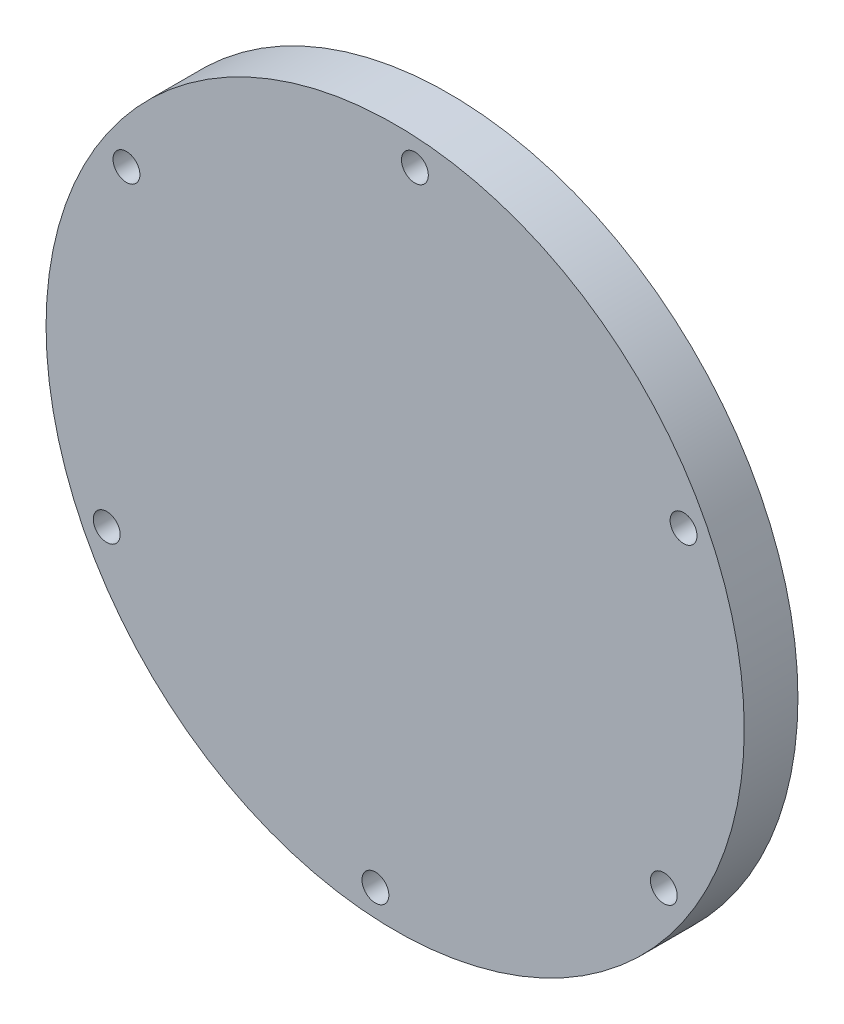
SolidWorks part; units mm, degrees
ref_plane "前视基准面" through (0, 0, 0) normal (0, 0, 1) x (1, 0, 0)
ref_plane "上视基准面" through (0, 0, 0) normal (0, 1, 0) x (1, 0, 0)
ref_plane "右视基准面" through (0, 0, 0) normal (1, 0, 0) x (0, 0, -1)
other "Configuration Table"
sketch "草图1" plane through (0, 0, 0) normal (0, 0, 1) x (1, 0, 0)
  circle A0 centre (0, 0) radius 65
  circle A1 centre (0, 0) radius 55
  circle A2 centre (0, 0) radius 60
  dimension "D1" = 130
  dimension "D2" = 110
  dimension "D3" = 120
extrude "凸台-拉伸1" add sketch "草图1" along normal blind 10 contours A0 A2 | A2 A1 | A1
sketch "草图2" plane through (0, 0, 0) normal (0, 0, -1) x (-1, 0, 0)
  circle A0 centre (-3.6755, 59.8873) radius 2.5
  circle A1 centre (0, 0) radius 60
  circle A2 centre (0, 0) radius 60
  circle A3 centre (0, 0) radius 55
  circle A4 centre (0, 0) radius 55
  circle A5 centre (0, 0) radius 65
  circle A6 centre (0, 0) radius 65
  circle A7 centre (50.0262, 33.1268) radius 2.5
  circle A8 centre (53.7017, -26.7606) radius 2.5
  circle A9 centre (3.6755, -59.8873) radius 2.5
  circle A10 centre (-50.0262, -33.1268) radius 2.5
  circle A11 centre (-53.7017, 26.7606) radius 2.5
  point P23 (0, 0)
  dimension "D4" = 5
  dimension "D1" = 0
  dimension "D2" = 0
  dimension "D3" = 0
  dimension "D5" = 6
extrude "切除-拉伸1" cut sketch "草图2" against normal up to next contours A0 | A11 | A10 | A9 | A8 | A7
sketch "草图3" plane through (0, 0, 0) normal (0, 0, -1) x (-1, 0, 0)
  circle A0 centre (-3.6755, 59.8873) radius 4
  circle A1 centre (-3.6755, 59.8873) radius 2.5
  circle A2 centre (-3.6755, 59.8873) radius 2.5
  circle A3 centre (50.0262, 33.1268) radius 4
  circle A4 centre (53.7017, -26.7606) radius 4
  circle A5 centre (3.6755, -59.8873) radius 4
  circle A6 centre (-50.0262, -33.1268) radius 4
  circle A7 centre (-53.7017, 26.7606) radius 4
  point P16 (0, 0)
  dimension "D2" = 8
  dimension "D1" = 0
  dimension "D3" = 6
extrude "切除-拉伸2" cut sketch "草图3" against normal blind 5
